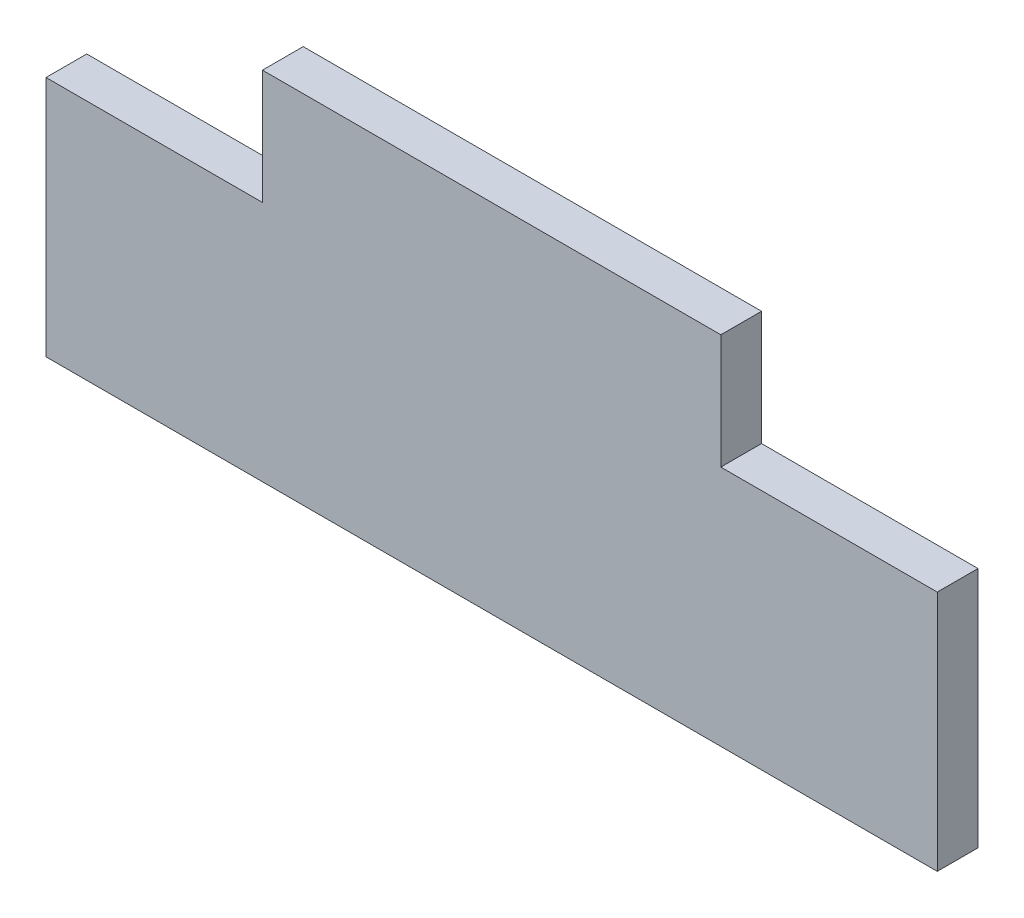
SolidWorks part; units mm, degrees
material "Rubber"
ref_plane "Front Plane" through (0, 0, 0) normal (0, 0, 1) x (1, 0, 0)
ref_plane "Top Plane" through (0, 0, 0) normal (0, 1, 0) x (1, 0, 0)
ref_plane "Right Plane" through (0, 0, 0) normal (1, 0, 0) x (0, 0, -1)
sketch "Sketch1" plane through (0, 0, 0) normal (0, 0, 1) x (1, 0, 0)
  line L8 (0, 0) -> (35, 0)
  line L9 (35, 0) -> (35, 9.5)
  line L10 (35, 9.5) -> (26.5, 9.5)
  line L11 (26.5, 9.5) -> (26.5, 14)
  line L12 (26.5, 14) -> (8.5, 14)
  line L13 (8.5, 14) -> (8.5, 9.5)
  line L14 (8.5, 9.5) -> (0, 9.5)
  line L15 (0, 9.5) -> (0, 0)
  dimension "D1" = 35
  dimension "D2" = 14
  dimension "D3" = 8.5
  dimension "D4" = 8.5
  dimension "D5" = 4.5
  dimension "D6" = 4.5
extrude "Boss-Extrude1" add sketch "Sketch1" along normal blind 1.6 contours L14 L15 L8 L9 L10 L11 L12 L13
